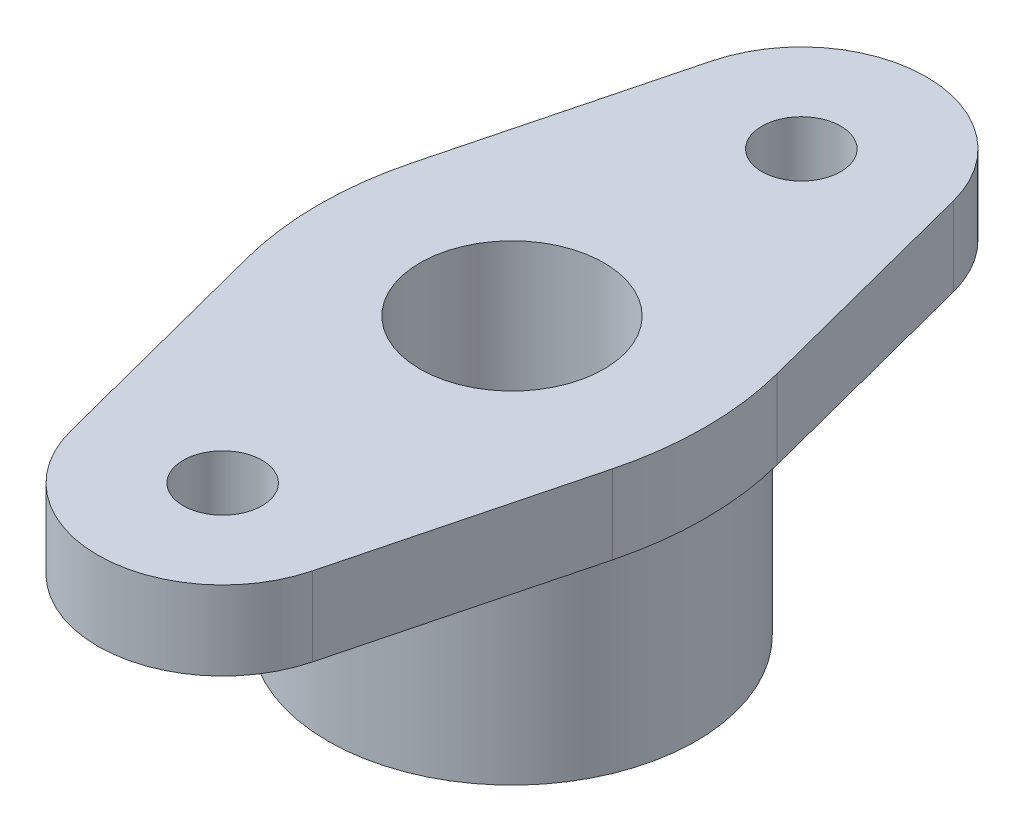
SolidWorks part; units mm, degrees
ref_plane "Front Plane" through (0, 0, 0) normal (0, 0, 1) x (1, 0, 0)
ref_plane "Top Plane" through (0, 0, 0) normal (0, 1, 0) x (1, 0, 0)
ref_plane "Right Plane" through (0, 0, 0) normal (1, 0, 0) x (0, 0, -1)
sketch "Sketch7" plane through (0, 0, 0) normal (0, 1, 0) x (1, 0, 0)
  line L0 (0, 48.4293) -> (0, -55.7513) construction
  line L1 (-32.4257, 0) -> (73.8469, 0) construction
  line L2 (18.3952, 48.7557) -> (31, 0)
  line L3 (-18.3952, 48.7557) -> (-31, 0)
  line L4 (18.3952, 48.7557) -> (31, 0)
  line L5 (-18.3952, 48.7557) -> (-31, 0)
  line L6 (0, -48.4293) -> (0, 55.7513) construction
  line L7 (-18.3952, -48.7557) -> (-31, 0)
  line L8 (18.3952, -48.7557) -> (31, 0)
  line L9 (-18.3952, -48.7557) -> (-31, 0)
  line L10 (18.3952, -48.7557) -> (31, 0)
  circle A0 centre (0, 44) radius 6
  arc A1 (18.3952, 48.7557) -> (-18.3952, 48.7557) centre (0, 44) ccw
  arc A2 (18.3952, -48.7557) -> (-18.3952, -48.7557) centre (0, -44) cw
  circle A3 centre (0, -44) radius 6
  circle A4 centre (0, 0) radius 14
  dimension "D1" = 38
  dimension "D2" = 12
  dimension "D5" = 28
  dimension "D3" = 88
  dimension "D4" = 62
extrude "Boss-Extrude2" add sketch "Sketch7" along normal blind 12 contours A2 L8 L2 A1 L3 L7 A4 A0 A3
fillet "Fillet3" radius 50 2 edges at (-31, 6, 0) (31, 6, 0)
sketch "Sketch8" plane through (0, 0, 0) normal (1, 0, 0) x (0, 0, -1)
  line L0 (0, 25.4525) -> (0, -35.5246) construction
  line L1 (14, 0) -> (28, 0)
  line L2 (28, 0) -> (28, -30)
  line L3 (28, -30) -> (14, -21.9171)
  line L4 (14, -21.9171) -> (14, 0)
  dimension "D1" = 30
  dimension "D2" = 28
  dimension "D3" = 60
revolve "Revolve2" add sketch "Sketch8" angle 360 about L0
